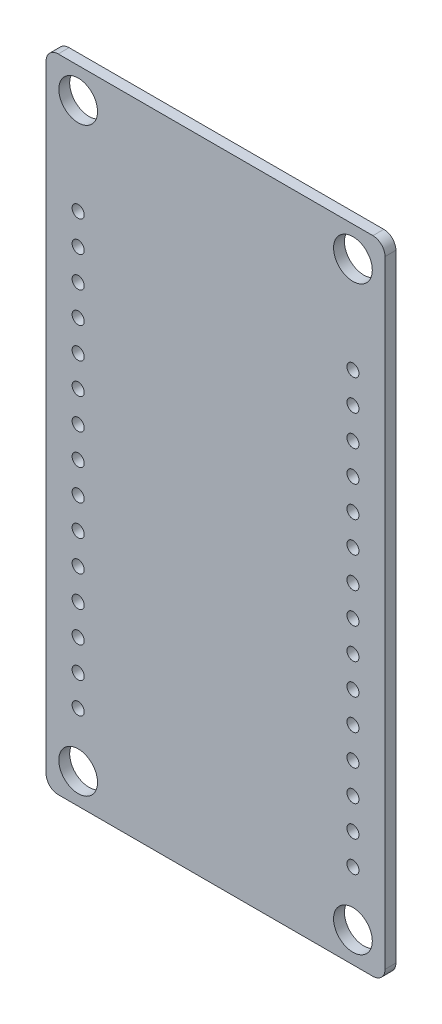
SolidWorks part; units mm, degrees
ref_plane "Plano frontal" through (0, 0, 0) normal (0, 0, 1) x (1, 0, 0)
ref_plane "Plano superior" through (0, 0, 0) normal (0, 1, 0) x (1, 0, 0)
ref_plane "Plano direito" through (0, 0, 0) normal (1, 0, 0) x (0, 0, -1)
sketch "Esboço1" plane through (0, 0, 0) normal (0, 0, 1) x (1, 0, 0)
  line L1 (14, -26.5) -> (-14, -26.5)
  line L2 (14, -26.5) -> (14, 26.5)
  line L3 (14, 26.5) -> (-14, 26.5)
  line L4 (-14, -26.5) -> (-14, 26.5)
  line L5 (14, -26.5) -> (-14, 26.5) construction
  line L6 (14, 26.5) -> (-14, -26.5) construction
  point P0 (0, 0)
  dimension "D1" = 28
  dimension "D2" = 53
extrude "Ressalto-extrusão1" add sketch "Esboço1" along normal mid plane 0.9
sketch "Esboço4" plane through (0, 0, 0.45) normal (0, 0, 1) x (1, 0, 0)
  line L0 (-14, 26.5) -> (-14, -26.5) construction
  line L1 (-14, -26.5) -> (14, -26.5) construction
  line L2 (0, -0.495) -> (0, 0.495) construction
  line L3 (0.495, 0) -> (-0.495, 0) construction
  circle A0 centre (-11.35, -24) radius 1.6
  circle A1 centre (11.35, -24) radius 1.6
  circle A2 centre (11.35, 24) radius 1.6
  circle A3 centre (-11.35, 24) radius 1.6
  dimension "D1" = 3.2
  dimension "D2" = 2.65
  dimension "D3" = 2.5
extrude "Corte-extrusão1" cut sketch "Esboço4" against normal up to next
sketch "Esboço5" plane through (0, 0, 0.45) normal (0, 0, 1) x (1, 0, 0)
  line L0 (-11.35, -24) -> (-11.35, 24) construction
  line L1 (0, -0.495) -> (0, 0.495) construction
  circle A0 centre (-11.35, -19.5) radius 0.5
  circle A16 centre (-11.35, -24) radius 1.6 construction
  circle A30 centre (11.35, -19.5) radius 0.5
  dimension "D2" = 1
  dimension "D1" = 4.5
extrude "Corte-extrusão2" cut sketch "Esboço5" against normal up to next
pattern_linear "Padrão linear1" count 15 spacing 2.54 along (0, 1, 0) of "Corte-extrusão2"
fillet "Filete1" radius 1 4 edges at (-14, -26.5, 0) (14, -26.5, 0) (14, 26.5, 0) (-14, 26.5, 0)
